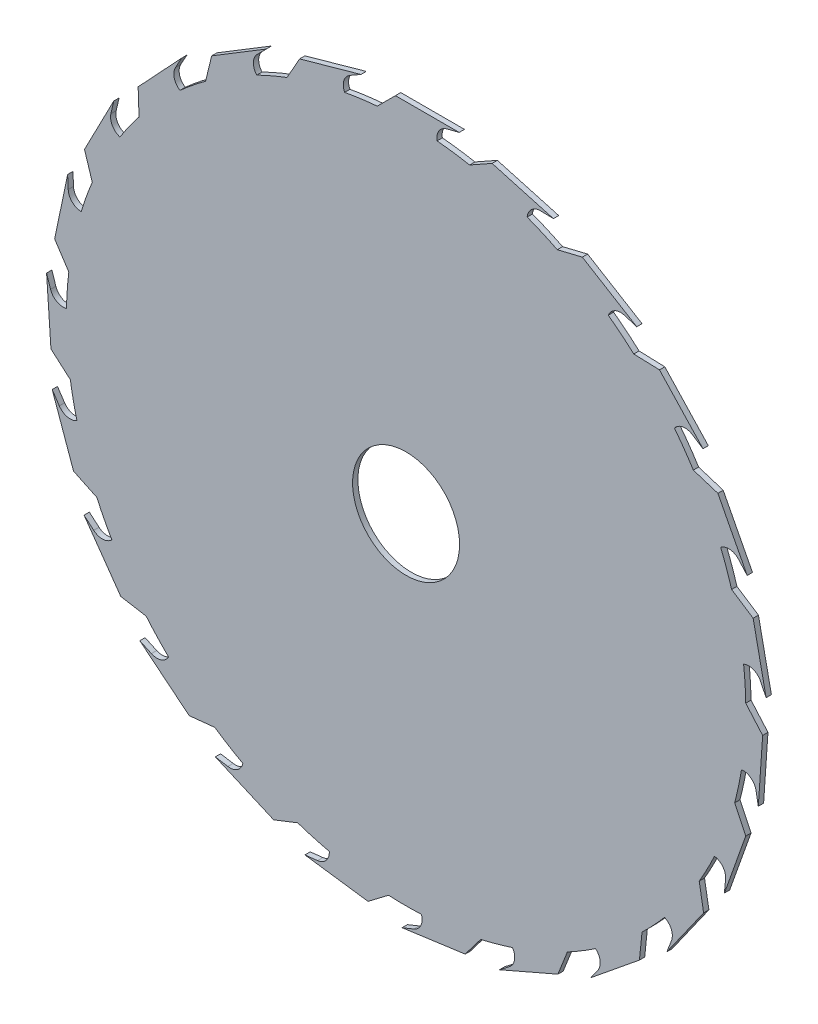
SolidWorks part; units mm, degrees
ref_plane "Front Plane" through (0, 0, 0) normal (0, 0, 1) x (1, 0, 0)
ref_plane "Top Plane" through (0, 0, 0) normal (0, 1, 0) x (1, 0, 0)
ref_plane "Right Plane" through (0, 0, 0) normal (1, 0, 0) x (0, 0, -1)
sketch "Sketch1" plane through (0, 0, 0) normal (0, 0, 1) x (1, 0, 0)
  circle A0 centre (0, 0) radius 101.6
  dimension "D1" = 203.2
extrude "Boss-Extrude1" add sketch "Sketch1" along normal blind 1.5875 contours A0
sketch "Sketch2" plane through (0, 0, 1.5875) normal (0, 0, 1) x (1, 0, 0)
  circle A0 centre (0, 0) radius 16.002
  dimension "D1" = 32.004
extrude "Cut-Extrude1" cut sketch "Sketch2" against normal up to next
sketch "Sketch4" plane through (0, 0, 1.5875) normal (0, 0, 1) x (1, 0, 0)
  line L0 (-9.525, 100.33) -> (-3.175, 106.68)
  line L1 (-3.175, 106.68) -> (15.875, 106.68)
  line L2 (15.875, 106.68) -> (12.1813, 105.7459)
  line L3 (9.525, 100.33) -> (-9.525, 100.33)
  arc A0 (12.1813, 105.7459) -> (9.525, 100.33) centre (13.1512, 101.9108) ccw
  point P6 (0, 0)
  point P8 (0, 100.33)
  point P9 (0, 0)
  dimension "D1" = 3.81
  dimension "D7" = 1.5808
  dimension "D2" = 19.05
  dimension "D3" = 6.35
  dimension "D4" = 19.05
  dimension "D5" = 106.68
  dimension "D6" = 45
extrude "Boss-Extrude2" add sketch "Sketch4" against normal up to surface (1.5875 mm away) up to face at (16.002, 0, 0)
pattern_circular "CirPattern1" count 23 over 360 about axis through (0, 0, 0) along (0, 0, 1) of "Boss-Extrude2"
